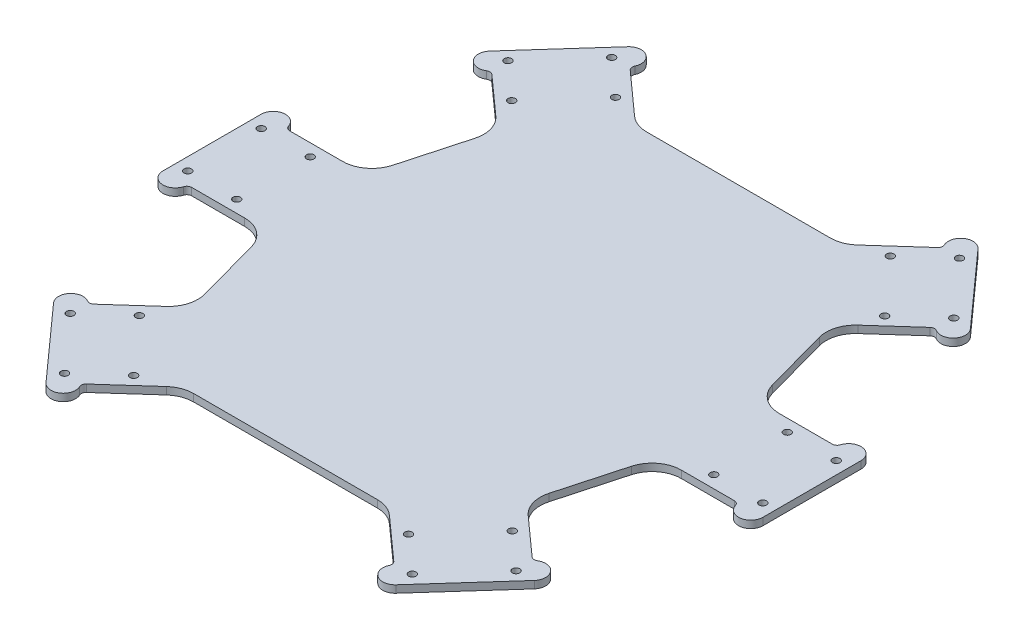
SolidWorks part; units mm, degrees
ref_plane "Front Plane" through (0, 0, 0) normal (0, 0, 1) x (1, 0, 0)
ref_plane "Top Plane" through (0, 0, 0) normal (0, 1, 0) x (1, 0, 0)
ref_plane "Right Plane" through (0, 0, 0) normal (1, 0, 0) x (0, 0, -1)
sketch "Sketch2" plane through (0, 0, 0) normal (0, 1, 0) x (1, 0, 0)
  line L0 (-122.5, 0) -> (153.1027, 0) construction
  line L1 (77.6041, 28.8181) -> (70.352, 55.1894)
  line L2 (37.5, 92.5) -> (-37.5, 92.5)
  line L4 (-77.6041, -28.8181) -> (-70.352, -55.1894)
  line L5 (-37.5, -92.5) -> (37.5, -92.5)
  line L7 (0, 115.175) -> (0, -107.9646) construction
  line L8 (-45.5104, 95.5651) -> (-62.7471, 111.0182)
  line L9 (-71.4647, 118.8339) -> (-98.1662, 89.0508)
  line L10 (-89.4485, 81.2351) -> (-73.9121, 67.3062)
  line L11 (-93.0534, 111.3279) -> (-54.3547, 76.6333) construction
  line L12 (-70.352, 55.1894) -> (-77.6041, 28.8181)
  line L13 (-68.3831, 62.3493) -> (-42.0916, 92.5) construction
  line L14 (-68.3831, 62.3493) -> (27.3728, 410.5524) construction
  line L15 (-42.0916, 92.5) -> (-60.0916, 92.5) construction
  line L16 (68.3831, 62.3493) -> (42.0916, 92.5) construction
  line L17 (73.4983, 120.657) -> (-27.3728, 410.5524) construction
  line L18 (93.0534, 111.3279) -> (54.3547, 76.6333) construction
  line L19 (71.4647, 118.8339) -> (98.1662, 89.0508)
  line L20 (89.4485, 81.2351) -> (73.9121, 67.3062)
  line L21 (45.5104, 95.5651) -> (62.7471, 111.0182)
  line L22 (45.5104, -95.5651) -> (62.7471, -111.0182)
  line L23 (71.4647, -118.8339) -> (98.1662, -89.0508)
  line L24 (89.4485, -81.2351) -> (73.9121, -67.3062)
  line L25 (-45.5104, -95.5651) -> (-62.7471, -111.0182)
  line L26 (-71.4647, -118.8339) -> (-98.1662, -89.0508)
  line L27 (-89.4485, -81.2351) -> (-73.9121, -67.3062)
  line L28 (-68.3831, -62.3493) -> (-42.0916, -92.5) construction
  line L29 (-60.1578, -92.5) -> (27.3728, -410.5524) construction
  line L30 (-93.0534, -111.3279) -> (-54.3547, -76.6333) construction
  line L31 (73.4983, -120.657) -> (-27.3728, -410.5524) construction
  line L32 (93.0534, -111.3279) -> (54.3547, -76.6333) construction
  line L33 (68.3831, -62.3493) -> (42.0916, -92.5) construction
  line L34 (70.352, -55.1894) -> (77.6041, -28.8181)
  line L36 (-89.1746, -20) -> (-110.7918, -20)
  line L37 (-122.5, -20) -> (-122.5, 20)
  line L38 (-110.7918, 20) -> (-89.1746, 20)
  line L39 (110.7918, 20) -> (89.1746, 20)
  line L40 (122.5, -20) -> (122.5, 20)
  line L41 (89.1746, -20) -> (110.7918, -20)
  circle A0 centre (-91.0386, 89.3759) radius 1.5
  circle A1 centre (-71.0125, 111.7132) radius 1.5
  arc A2 (-98.1662, 89.0508) -> (-91.8292, 81.4508) centre (-94.4433, 85.7131) ccw
  arc A3 (-71.4647, 118.8339) -> (-63.2205, 113.3613) centre (-67.7418, 115.4962) cw
  arc A4 (-63.2205, 113.3613) -> (-62.7471, 111.0182) centre (-61.412, 112.5074) ccw
  arc A5 (-91.8292, 81.4508) -> (-89.4485, 81.2351) centre (-90.7836, 79.746) cw
  arc A6 (-45.5104, 95.5651) -> (-37.5, 92.5) centre (-37.5, 104.5) ccw
  arc A7 (-73.9121, 67.3062) -> (-70.352, 55.1894) centre (-81.9225, 58.3713) cw
  circle A8 centre (91.0386, 89.3759) radius 1.5
  circle A9 centre (71.0125, 111.7132) radius 1.5
  arc A10 (71.4647, 118.8339) -> (63.2205, 113.3613) centre (67.7418, 115.4962) ccw
  arc A11 (98.1662, 89.0508) -> (91.8292, 81.4508) centre (94.4433, 85.7131) cw
  arc A12 (45.5104, 95.5651) -> (37.5, 92.5) centre (37.5, 104.5) cw
  arc A13 (73.9121, 67.3062) -> (70.352, 55.1894) centre (81.9225, 58.3713) ccw
  arc A14 (63.2205, 113.3613) -> (62.7471, 111.0182) centre (61.412, 112.5074) cw
  arc A15 (91.8292, 81.4508) -> (89.4485, 81.2351) centre (90.7836, 79.746) ccw
  arc A16 (63.2205, -113.3613) -> (62.7471, -111.0182) centre (61.412, -112.5074) ccw
  arc A17 (45.5104, -95.5651) -> (37.5, -92.5) centre (37.5, -104.5) ccw
  arc A18 (71.4647, -118.8339) -> (63.2205, -113.3613) centre (67.7418, -115.4962) cw
  arc A19 (91.8292, -81.4508) -> (89.4485, -81.2351) centre (90.7836, -79.746) cw
  arc A20 (98.1662, -89.0508) -> (91.8292, -81.4508) centre (94.4433, -85.7131) ccw
  arc A21 (73.9121, -67.3062) -> (70.352, -55.1894) centre (81.9225, -58.3713) cw
  arc A22 (-45.5104, -95.5651) -> (-37.5, -92.5) centre (-37.5, -104.5) cw
  arc A23 (-91.8292, -81.4508) -> (-89.4485, -81.2351) centre (-90.7836, -79.746) ccw
  arc A24 (-63.2205, -113.3613) -> (-62.7471, -111.0182) centre (-61.412, -112.5074) cw
  arc A25 (-71.4647, -118.8339) -> (-63.2205, -113.3613) centre (-67.7418, -115.4962) ccw
  arc A26 (-98.1662, -89.0508) -> (-91.8292, -81.4508) centre (-94.4433, -85.7131) cw
  arc A27 (-73.9121, -67.3062) -> (-70.352, -55.1894) centre (-81.9225, -58.3713) ccw
  circle A28 centre (91.0386, -89.3759) radius 1.5
  circle A29 centre (71.0125, -111.7132) radius 1.5
  circle A30 centre (-71.0125, -111.7132) radius 1.5
  circle A31 centre (-91.0386, -89.3759) radius 1.5
  circle A32 centre (-117.41, -15) radius 1.5
  circle A33 centre (-117.41, 15) radius 1.5
  arc A34 (-122.5, 20) -> (-112.7084, 21.4286) centre (-117.5, 20) cw
  arc A35 (-122.5, -20) -> (-112.7084, -21.4286) centre (-117.5, -20) ccw
  arc A36 (-112.7084, 21.4286) -> (-110.7918, 20) centre (-110.7918, 22) ccw
  arc A37 (-112.7084, -21.4286) -> (-110.7918, -20) centre (-110.7918, -22) cw
  arc A38 (-89.1746, 20) -> (-77.6041, 28.8181) centre (-89.1746, 32) ccw
  arc A39 (-89.1746, -20) -> (-77.6041, -28.8181) centre (-89.1746, -32) cw
  arc A40 (89.1746, 20) -> (77.6041, 28.8181) centre (89.1746, 32) cw
  arc A41 (112.7084, 21.4286) -> (110.7918, 20) centre (110.7918, 22) cw
  arc A42 (122.5, 20) -> (112.7084, 21.4286) centre (117.5, 20) ccw
  arc A43 (122.5, -20) -> (112.7084, -21.4286) centre (117.5, -20) cw
  arc A44 (112.7084, -21.4286) -> (110.7918, -20) centre (110.7918, -22) ccw
  arc A45 (89.1746, -20) -> (77.6041, -28.8181) centre (89.1746, -32) ccw
  circle A46 centre (117.41, -15) radius 1.5
  circle A47 centre (117.41, 15) radius 1.5
  ellipse E0 centre (0, 0) end of major axis (0, 92.5) minor radius 81.6588 construction
  point P35 (-90.7204, 82.3754)
  point P131 (-112.5, -20)
  point P132 (-112.5, 20)
  point P134 (-112.5, 20)
  point P137 (-112.5, -20)
  point P138 (-80.0291, 20)
  point P139 (-80.0291, -20)
  dimension "D13" = 3
  dimension "D14" = 5.09
  dimension "D15" = 15
  dimension "D17" = 5
  dimension "D18" = 5
  dimension "D20" = 2
  dimension "D21" = 12
  dimension "D23" = 3
  dimension "D24" = 30
  dimension "D26" = 5
  dimension "D27" = 5
  dimension "D28" = 2
  dimension "D12" = 12
  dimension "D2" = 185
  dimension "D3" = 40.0038
  dimension "D4" = 74.624
  dimension "D5" = 105.376
  dimension "D6" = 40
  dimension "D7" = 105.376
  dimension "D8" = 116.501
  dimension "D9" = 40
  dimension "D10" = 40
  dimension "D11" = 138.123
  dimension "D16" = 20
  dimension "D22" = 75
  dimension "D25" = 5.09
  dimension "D29" = 245
extrude "Boss-Extrude1" add sketch "Sketch2" along normal blind 3
sketch "Sketch5" plane through (0, 3, 0) normal (0, 1, 0) x (1, 0, 0)
  line L0 (0, 82.5) -> (0, -82.5)
  line L1 (8.5, 81.7996) -> (8.5, -81.7996)
  line L2 (17, 79.6613) -> (17, -79.6613)
  line L3 (25.5, 75.9639) -> (25.5, -75.9639)
  line L4 (34, 70.4624) -> (34, -70.4624)
  line L5 (42.5, 62.6835) -> (42.5, -62.6835)
  line L6 (51, 51.6075) -> (51, -51.6075)
  line L7 (59.5, 34.1654) -> (59.5, -34.1654)
  line L8 (-8.5, 81.7996) -> (-8.5, -81.7996)
  line L9 (-17, 79.6613) -> (-17, -79.6613)
  line L10 (-25.5, 75.9639) -> (-25.5, -75.9639)
  line L11 (-34, 70.4624) -> (-34, -70.4624)
  line L12 (-42.5, 62.6835) -> (-42.5, -62.6835)
  line L13 (-51, 51.6075) -> (-51, -51.6075)
  line L14 (-59.5, 34.1654) -> (-59.5, -34.1654)
  ellipse E0 centre (0, 0) end of major axis (0, -82.5) minor radius 65.3689
  dimension "D1" = 165
  dimension "D4" = 8.5
  dimension "D5" = 8.5
  dimension "D2" = 8
  dimension "D3" = 8
sketch "Sketch7" plane through (0, 3, 0) normal (0, 1, 0) x (1, 0, 0)
  circle A0 centre (-91.0386, 89.3759) radius 1.5 construction
  circle A1 centre (-71.0125, 111.7132) radius 1.5 construction
  circle A2 centre (-91.0386, 89.3759) radius 1.5
  circle A3 centre (-71.0125, 111.7132) radius 1.5
  circle A4 centre (-76.147, 76.0252) radius 1.5
  circle A5 centre (-56.121, 98.3625) radius 1.5
  dimension "D1" = 2
  dimension "D2" = 2
extrude "Cut-Extrude4" cut sketch "Sketch7" against normal blind 10 contours A4 | A5
mirror "Mirror1" about plane through (0, 0, 0) normal (1, 0, 0) of "Cut-Extrude4"
mirror "Mirror2" about plane through (0, 0, 0) normal (0, 0, 1) of "Mirror1", "Cut-Extrude4"
sketch "Sketch8" plane through (0, 3, 0) normal (0, 1, 0) x (1, 0, 0)
  circle A0 centre (-117.41, 15) radius 1.5 construction
  circle A1 centre (-117.41, -15) radius 1.5 construction
  circle A2 centre (-117.41, 15) radius 1.5
  circle A3 centre (-117.41, -15) radius 1.5
  circle A4 centre (-97.41, -15) radius 1.5
  circle A5 centre (-97.41, 15) radius 1.5
  dimension "D1" = 2
extrude "Cut-Extrude5" cut sketch "Sketch8" against normal blind 10
mirror "Mirror3" about plane through (0, 0, 0) normal (1, 0, 0) of "Cut-Extrude5"
sketch "Sketch9" plane through (0, 3, 0) normal (0, 1, 0) x (1, 0, 0)
  line L0 (0, 139.8126) -> (0, -160.3192) construction
  ellipse E0 centre (0, 0) end of major axis (0, 127.3071) minor radius 110
  point P4 (0, -127.3071)
  point P10 (0, 167.3071)
  dimension "D1" = 220
  dimension "D2" = 40
